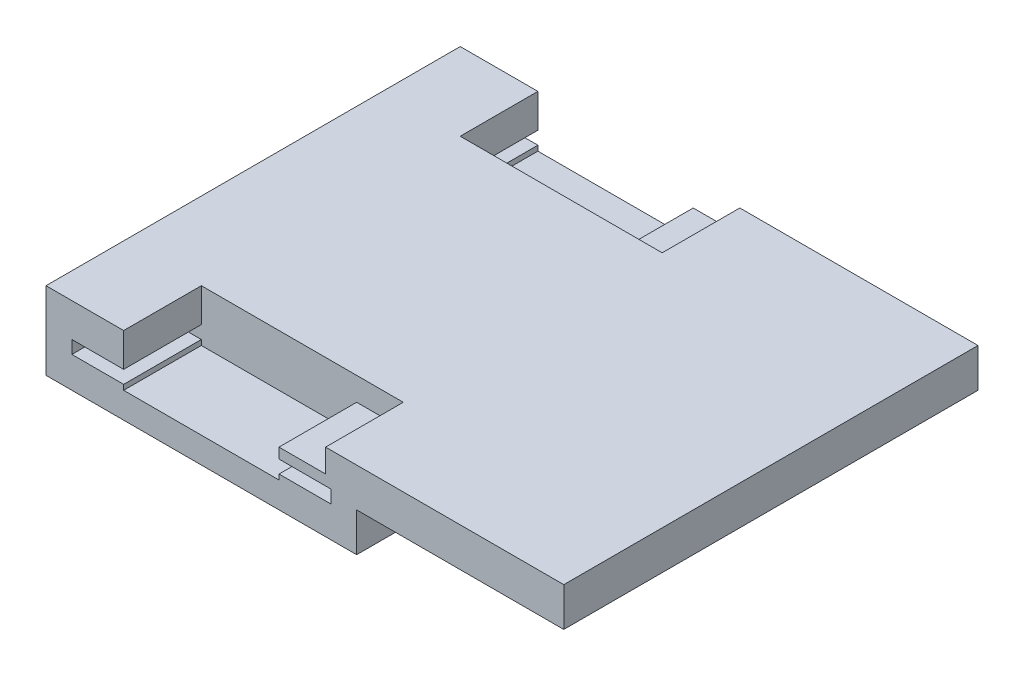
SolidWorks part; units mm, degrees
ref_plane "Front Plane" through (0, 0, 0) normal (0, 0, 1) x (1, 0, 0)
ref_plane "Top Plane" through (0, 0, 0) normal (0, 1, 0) x (1, 0, 0)
ref_plane "Right Plane" through (0, 0, 0) normal (1, 0, 0) x (0, 0, -1)
sketch "Sketch1" plane through (0, 0, 0) normal (0, 1, 0) x (1, 0, 0)
  line L1 (-160, 80) -> (160, 80)
  line L2 (-160, 80) -> (-160, -80)
  line L3 (-160, -80) -> (160, -80)
  line L4 (160, 80) -> (160, -80)
  line L5 (-160, 80) -> (160, -80) construction
  line L6 (-160, -80) -> (160, 80) construction
  point P0 (0, 0)
  dimension "D1" = 320
  dimension "D2" = 160
extrude "Boss-Extrude1" add sketch "Sketch1" along normal blind 20
sketch "Sketch2" plane through (0, 20, 0) normal (0, 1, 0) x (1, 0, 0)
  line L0 (-160, -80) -> (160, -80) construction
  line L1 (-130, -80) -> (-70, -80)
  line L2 (-130, -80) -> (-130, -50)
  line L3 (-130, -50) -> (-70, -50)
  line L4 (-70, -80) -> (-70, -50)
  line L5 (-160, 80) -> (-160, -80) construction
  dimension "D1" = 60
  dimension "D2" = 30
  dimension "D3" = 30
extrude "Cut-Extrude1" cut sketch "Sketch2" against normal blind 28
sketch "Sketch3" plane through (0, 0, 80) normal (0, 0, 1) x (1, 0, 0)
  line L0 (-130, 0) -> (-130, 20) construction
  line L1 (-130, 7) -> (-150, 7)
  line L2 (-130, 7) -> (-130, 2)
  line L3 (-130, 2) -> (-150, 2)
  line L4 (-150, 7) -> (-150, 2)
  line L5 (-160, 0) -> (-130, 0) construction
  line L6 (-70, 0) -> (-70, 20) construction
  line L7 (-70, 7) -> (-50, 7)
  line L8 (-70, 7) -> (-70, 2)
  line L9 (-70, 2) -> (-50, 2)
  line L10 (-50, 7) -> (-50, 2)
  line L11 (88, 0) -> (-88, 0) construction
  dimension "D1" = 2
  dimension "D2" = 5
  dimension "D3" = 20
  dimension "D4" = 20
  dimension "D5" = 5
  dimension "D6" = 2
extrude "Cut-Extrude3" cut sketch "Sketch3" against normal blind 30
mirror "Mirror2" about plane through (0, 0, 0) normal (1, 0, 0) of "Cut-Extrude1", "Cut-Extrude3"
mirror "Mirror3" about plane through (0, 0, 0) normal (0, 0, 1) of "Mirror2", "Cut-Extrude1", "Cut-Extrude3"
sketch "Sketch8" plane through (0, 0, -80) normal (0, 0, -1) x (-1, 0, 0)
  line L0 (-130, 7) -> (-130, 20) construction
  line L1 (-130, 11) -> (-148, 11)
  line L2 (-130, 11) -> (-130, 20)
  line L3 (-130, 20) -> (-148, 20)
  line L4 (-148, 11) -> (-148, 20)
  line L5 (-160, 20) -> (-130, 20) construction
  line L6 (-130, 7) -> (-150, 7) construction
  dimension "D1" = 18
  dimension "D2" = 4
extrude "Cut-Extrude6" cut sketch "Sketch8" against normal blind 30
sketch "Sketch9" plane through (0, 0, -80) normal (0, 0, -1) x (-1, 0, 0)
  line L0 (70, 20) -> (70, 7) construction
  line L1 (70, 11) -> (52, 11)
  line L2 (70, 11) -> (70, 20)
  line L3 (70, 20) -> (52, 20)
  line L4 (52, 11) -> (52, 20)
  line L5 (-70, 20) -> (70, 20) construction
  line L6 (50, 7) -> (70, 7) construction
  dimension "D1" = 18
  dimension "D2" = 4
extrude "Cut-Extrude7" cut sketch "Sketch9" against normal blind 30
sketch "Sketch10" plane through (0, 0, 0) normal (0, -1, 0) x (1, 0, 0)
  line L1 (-160, 80) -> (160, 80)
  line L2 (-160, 80) -> (-160, -80)
  line L3 (-160, -80) -> (160, -80)
  line L4 (160, 80) -> (160, -80)
extrude "Boss-Extrude2" add sketch "Sketch10" along normal blind 10
mirror "Mirror4" about plane through (0, 0, 0) normal (0, 0, 1) of "Cut-Extrude7", "Cut-Extrude6"
sketch "Sketch11" plane through (0, 0, -80) normal (0, 0, -1) x (-1, 0, 0)
  line L0 (-40, 20) -> (-40, 5)
  line L1 (-70, 20) -> (52, 20) construction
  line L2 (-40, 5) -> (40, 5)
  line L3 (40, 5) -> (40, -10)
  line L4 (160, -10) -> (-160, -10) construction
  line L5 (40, -10) -> (-160, -10)
  line L6 (-160, -10) -> (-160, 20)
  line L7 (-160, 20) -> (-40, 20)
  line L8 (0, 16.5) -> (0, -16.5) construction
  dimension "D1" = 15
  dimension "D2" = 40
  dimension "D3" = 40
extrude "Cut-Extrude8" cut sketch "Sketch11" against normal blind 238
